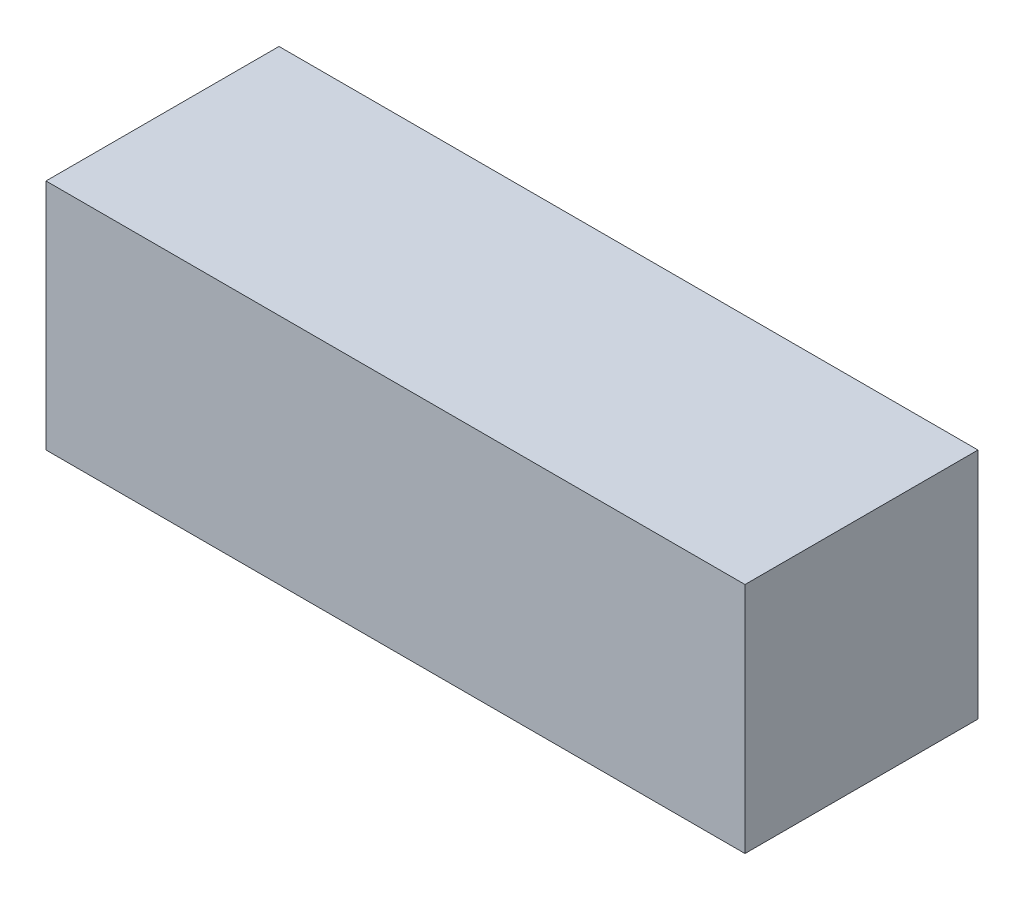
SolidWorks part; units mm, degrees
ref_plane "Front Plane" through (0, 0, 0) normal (0, 0, 1) x (1, 0, 0)
ref_plane "Top Plane" through (0, 0, 0) normal (0, 1, 0) x (1, 0, 0)
ref_plane "Right Plane" through (0, 0, 0) normal (1, 0, 0) x (0, 0, -1)
sketch "Sketch1" plane through (0, 0, 0) normal (0, 0, 1) x (1, 0, 0)
  line L1 (-0.75, -0.25) -> (0.75, -0.25)
  line L2 (-0.75, -0.25) -> (-0.75, 0.25)
  line L3 (-0.75, 0.25) -> (0.75, 0.25)
  line L4 (0.75, -0.25) -> (0.75, 0.25)
  line L5 (-0.75, -0.25) -> (0.75, 0.25) construction
  line L6 (-0.75, 0.25) -> (0.75, -0.25) construction
  point P0 (0, 0)
  dimension "D1" = 1.5
  dimension "D2" = 0.5
extrude "Extrude1" add sketch "Sketch1" along normal blind 0.5
